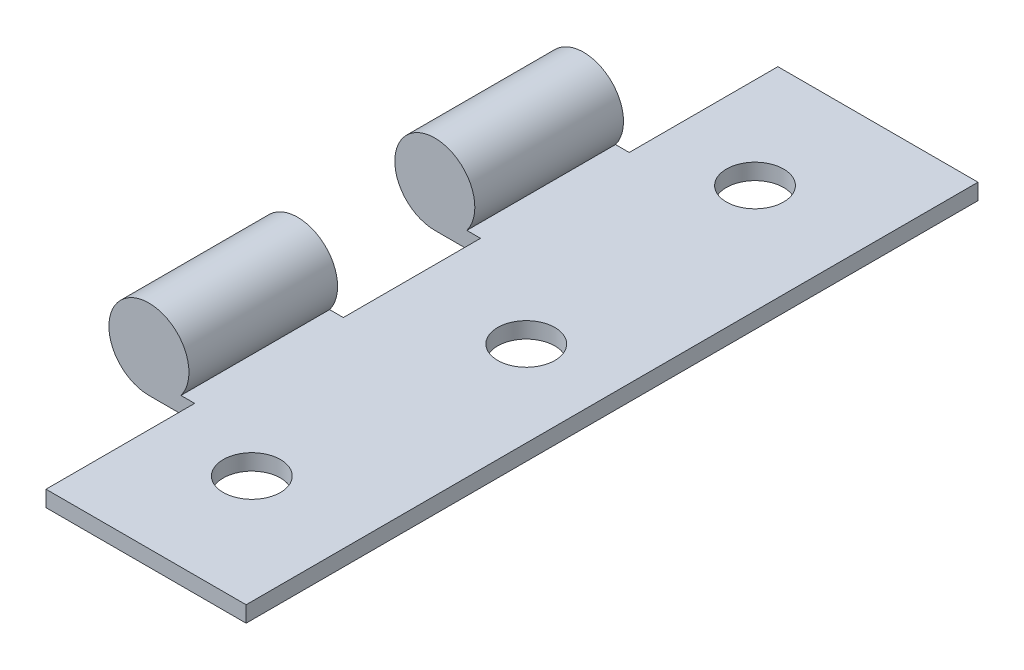
SolidWorks part; units mm, degrees
material "1060 Alloy"
ref_plane "Front Plane" through (0, 0, 0) normal (0, 0, 1) x (1, 0, 0)
ref_plane "Top Plane" through (0, 0, 0) normal (0, 1, 0) x (1, 0, 0)
ref_plane "Right Plane" through (0, 0, 0) normal (1, 0, 0) x (0, 0, -1)
sketch "Sketch1" plane through (0, 0, 0) normal (0, 0, 1) x (1, 0, 0)
  line L1 (0, 0) -> (21.5, 0)
  line L3 (2.8, 1.4) -> (21.5, 1.4)
  line L4 (21.5, 0) -> (21.5, 1.4)
  arc A0 (2.8, 1.4) -> (0, 0) centre (0, 3.5) ccw
  dimension "D1" = 7
  dimension "D2" = 21.5
  dimension "D3" = 1.4
extrude "Boss-Extrude1" add sketch "Sketch1" along normal blind 64
sketch "Sketch2" plane through (0, 0, 0) normal (0, 1, 0) x (1, 0, 0)
  circle A0 centre (12, -54) radius 2.5
  circle A1 centre (14, -32) radius 2.5
  circle A2 centre (12, -10) radius 2.5
  dimension "D1" = 5
  dimension "D2" = 5
  dimension "D3" = 5
  dimension "D4" = 12
  dimension "D5" = 10
  dimension "D6" = 44
  dimension "D7" = 22
  dimension "D8" = 2
extrude "Cut-Extrude2" cut sketch "Sketch2" along normal blind 5
sketch "Sketch3" plane through (0, 0, 0) normal (0, 1, 0) x (1, 0, 0)
  line L2 (-4, 0) -> (4, 0)
  line L3 (-4, 0) -> (-4, -13)
  line L4 (-4, -13) -> (4, -13)
  line L5 (4, 0) -> (4, -13)
  line L6 (-4, -26) -> (4, -26)
  line L7 (-4, -26) -> (-4, -38)
  line L8 (-4, -38) -> (4, -38)
  line L9 (4, -26) -> (4, -38)
  line L11 (-4, -51) -> (4, -51)
  line L12 (-4, -51) -> (-4, -64)
  line L13 (-4, -64) -> (4, -64)
  line L14 (4, -51) -> (4, -64)
  dimension "D1" = 13
  dimension "D2" = 12
  dimension "D3" = 13
  dimension "D4" = 13
  dimension "D5" = 13
  dimension "D6" = 8
  dimension "D7" = 4
extrude "Cut-Extrude3" cut sketch "Sketch3" along normal blind 15
